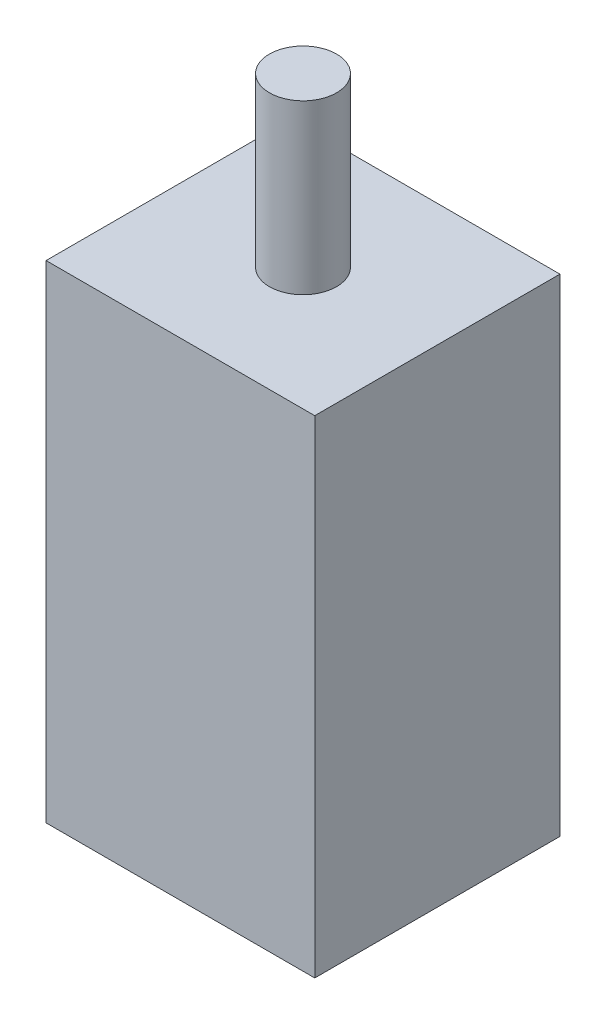
SolidWorks part; units mm, degrees
ref_plane "Alzado" through (0, 0, 0) normal (0, 0, 1) x (1, 0, 0)
ref_plane "Planta" through (0, 0, 0) normal (0, 1, 0) x (1, 0, 0)
ref_plane "Vista lateral" through (0, 0, 0) normal (1, 0, 0) x (0, 0, -1)
sketch "Croquis1" plane through (0, 0, 0) normal (0, 1, 0) x (1, 0, 0)
  line L1 (-7.1852, 11.3037) -> (8.8148, 11.3037)
  line L2 (-7.1852, 11.3037) -> (-7.1852, -3.2963)
  line L3 (-7.1852, -3.2963) -> (8.8148, -3.2963)
  line L4 (8.8148, 11.3037) -> (8.8148, -3.2963)
  dimension "D1" = 16
  dimension "D2" = 14.6
extrude "Saliente-Extruir1" add sketch "Croquis1" along normal blind 29 contours L2 L1 L4 L3
sketch "Croquis2" plane through (0, 29, 0) normal (0, 1, 0) x (1, 0, 0)
  circle A0 centre (0.8148, 4.0037) radius 2
extrude "Saliente-Extruir2" add sketch "Croquis2" along normal blind 10
